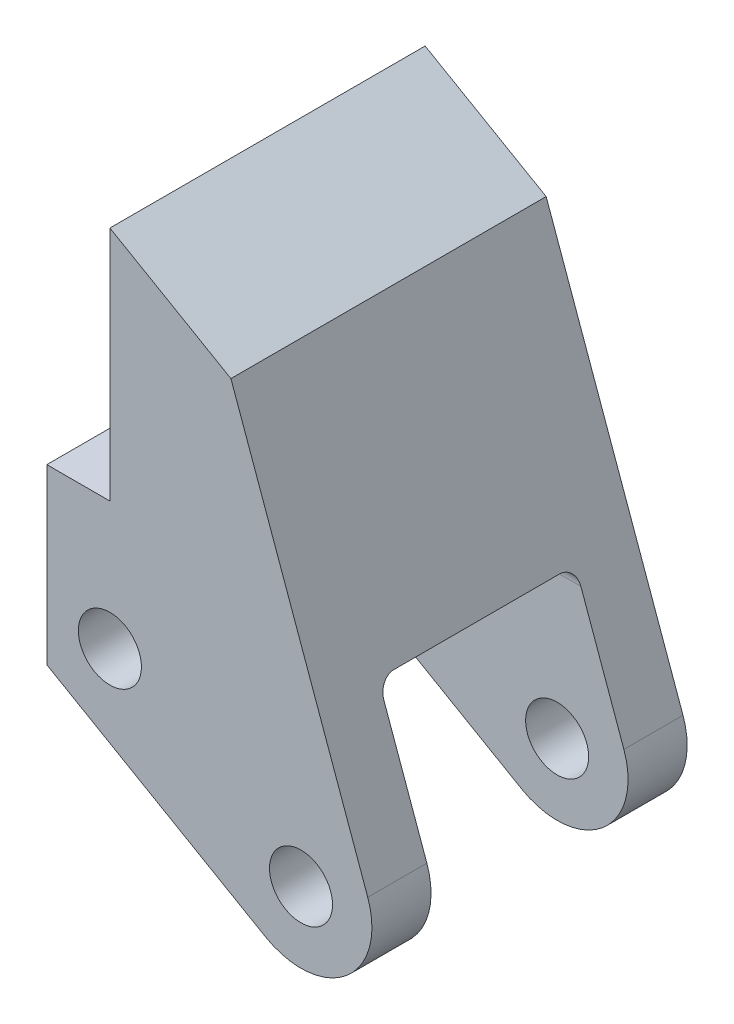
SolidWorks part; units mm, degrees
ref_plane "前视基准面" through (0, 0, 0) normal (0, 0, 1) x (1, 0, 0)
ref_plane "上视基准面" through (0, 0, 0) normal (0, 1, 0) x (1, 0, 0)
ref_plane "右视基准面" through (0, 0, 0) normal (1, 0, 0) x (0, 0, -1)
other "Configuration Table"
sketch "草图1" plane through (0, 0, 0) normal (0, 0, 1) x (1, 0, 0)
  line L0 (0, 0) -> (24.2487, -14) construction
  line L1 (-18.1891, 0) -> (27.668, 0) construction
  line L2 (0, 46.2265) -> (0, 16.2265)
  line L3 (0, 16.2265) -> (-8, 16.2265)
  line L4 (-8, 16.2265) -> (-8, -5.7735)
  line L5 (-8, -5.7735) -> (19.7487, -21.7942)
  line L6 (32.7185, -10.9565) -> (15.3565, 37.3604)
  line L7 (15.3565, 37.3604) -> (0, 46.2265)
  circle A0 centre (0, 0) radius 4
  circle A1 centre (24.2487, -14) radius 4
  arc A2 (19.7487, -21.7942) -> (32.7185, -10.9565) centre (24.2487, -14) ccw
  dimension "D1" = 30
  dimension "D2" = 9
  dimension "D10" = 18
  dimension "D8" = 8
  dimension "D9" = 8
  dimension "D3" = 5.7735
  dimension "D4" = 22
  dimension "D5" = 8
  dimension "D6" = 30
  dimension "D7" = 60
  dimension "D11" = 9
  dimension "D12" = 28
extrude "凸台-拉伸1" add sketch "草图1" along normal blind 40
sketch "草图2" plane through (-8, 0, 0) normal (-1, 0, 0) x (0, 0, 1)
  line L0 (20, 50.3036) -> (20, -24.8123) construction
  line L1 (0, 16.2265) -> (0, -5.7735) construction
  line L2 (7.5, 6.2265) -> (32.5, 6.2265)
  line L3 (40, 16.2265) -> (0, 16.2265) construction
  line L4 (40, 16.2265) -> (40, -5.7735) construction
  line L5 (7.5, 6.2265) -> (7.5, -24.8123)
  line L6 (7.5, -24.8123) -> (32.5, -24.8123)
  line L7 (32.5, -24.8123) -> (32.5, 6.2265)
  dimension "D1" = 10
  dimension "D2" = 7.5
  dimension "D3" = 7.5
extrude "切除-拉伸1" cut sketch "草图2" against normal through all
fillet "圆角3" radius 2 2 edges at (9.272, 6.2265, 7.5) (9.272, 6.2265, 32.5)
